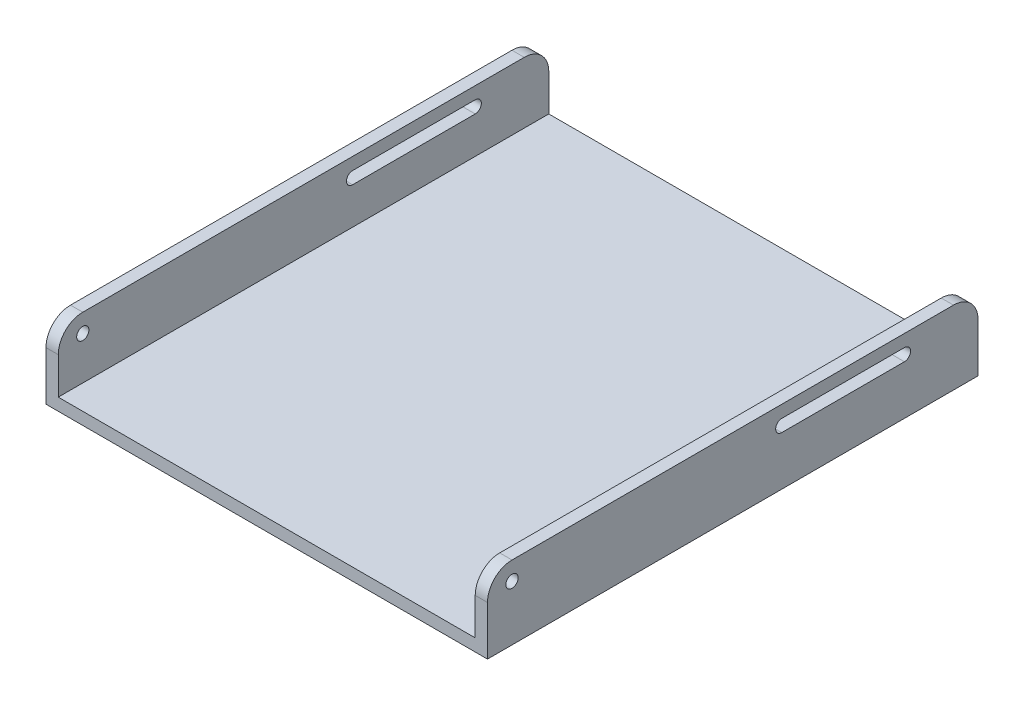
SolidWorks part; units mm, degrees
material "PVC 0.007 Plasticized"
ref_plane "Front Plane" through (0, 0, 0) normal (0, 0, 1) x (1, 0, 0)
ref_plane "Top Plane" through (0, 0, 0) normal (0, 1, 0) x (1, 0, 0)
ref_plane "Right Plane" through (0, 0, 0) normal (1, 0, 0) x (0, 0, -1)
sketch "Sketch1" plane through (0, 0, 0) normal (0, 0, 1) x (1, 0, 0)
  line L0 (-150, 0) -> (210, 0)
  line L1 (210, 0) -> (210, 60)
  line L2 (-150, 0) -> (-150, 60)
  dimension "D1" = 360
  dimension "D2" = 60
  dimension "D3" = 60
  dimension "D4" = 150
extrude "Extrude-Thin1" add sketch "Sketch1" along normal mid plane 400 thin thin type one direction wall 10
sketch "Sketch2" plane through (210, 0, 0) normal (1, 0, 0) x (0, 0, -1)
  line L0 (40, 45) -> (140, 45) construction
  line L1 (40, 50) -> (140, 50)
  line L2 (40, 40) -> (140, 40)
  line L3 (-200, 0) -> (200, 0) construction
  line L4 (200, 60) -> (200, 0) construction
  arc A0 (40, 50) -> (40, 40) centre (40, 45) ccw
  arc A1 (140, 40) -> (140, 50) centre (140, 45) ccw
  point P2 (90, 45)
  dimension "D1" = 45
  dimension "D2" = 10
  dimension "D3" = 100
  dimension "D4" = 60
extrude "Cut-Extrude1" cut sketch "Sketch2" against normal blind 364
fillet "Fillet1" radius 20 4 edges at (-145, 60, 200) (-145, 60, -200) (205, 60, 200) (205, 60, -200)
sketch "Sketch3" plane through (-150, 0, 0) normal (-1, 0, 0) x (0, 0, 1)
  line L0 (200, 0) -> (200, 40) construction
  line L1 (200, 0) -> (-200, 0) construction
  circle A0 centre (180, 45) radius 5
  dimension "D1" = 10
  dimension "D2" = 20
  dimension "D3" = 45
extrude "Cut-Extrude2" cut sketch "Sketch3" against normal through all
